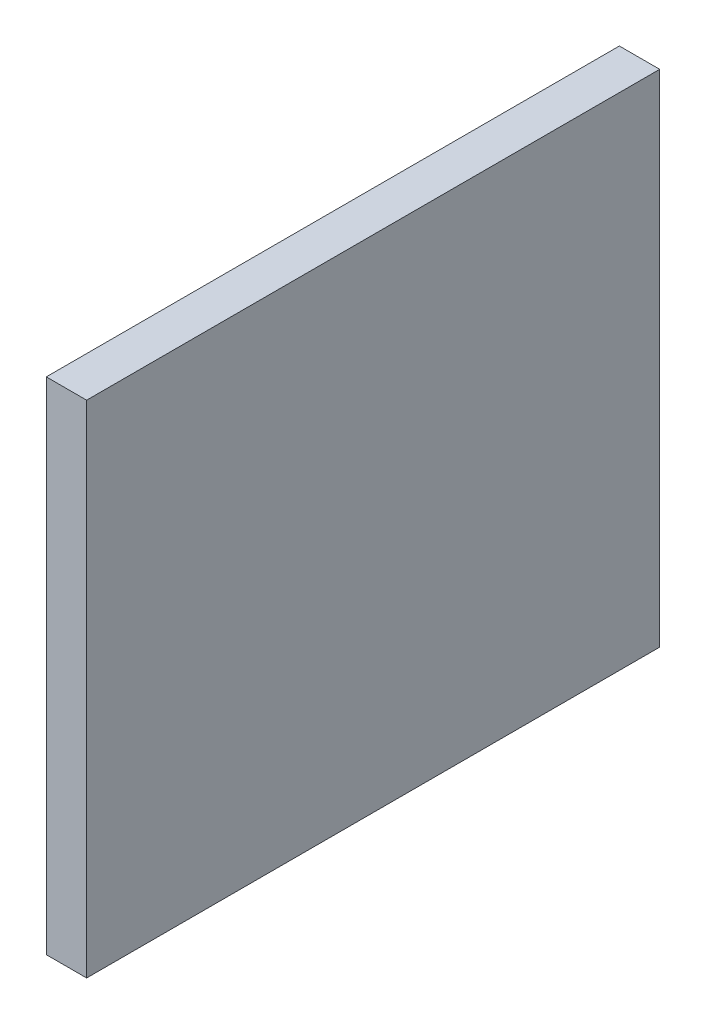
SolidWorks part; units mm, degrees
ref_plane "Alzado" through (0, 0, 0) normal (0, 0, 1) x (1, 0, 0)
ref_plane "Planta" through (0, 0, 0) normal (0, 1, 0) x (1, 0, 0)
ref_plane "Vista lateral" through (0, 0, 0) normal (1, 0, 0) x (0, 0, -1)
sketch "Croquis1" plane through (0, 0, 0) normal (0, 0, 1) x (1, 0, 0)
  line L1 (-5, -62) -> (5, -62)
  line L2 (-5, -62) -> (-5, 62)
  line L3 (-5, 62) -> (5, 62)
  line L4 (5, -62) -> (5, 62)
  line L5 (-5, -62) -> (5, 62) construction
  line L6 (-5, 62) -> (5, -62) construction
  point P0 (0, 0)
  dimension "D1" = 10
  dimension "D2" = 124
extrude "Saliente-Extruir3" add sketch "Croquis1" along normal blind 142
sketch "Croquis4" plane through (0, 0, 142) normal (0, 0, 1) x (1, 0, 0)
  line L0 (-2, 62) -> (-2, -62) construction
  line L1 (5, 62) -> (-5, 62) construction
  line L2 (-5, -62) -> (5, -62) construction
  line L3 (-5, 62) -> (-5, -62) construction
  text T0 "SOLIDWORKS 2026"
  dimension "D1" = 3
